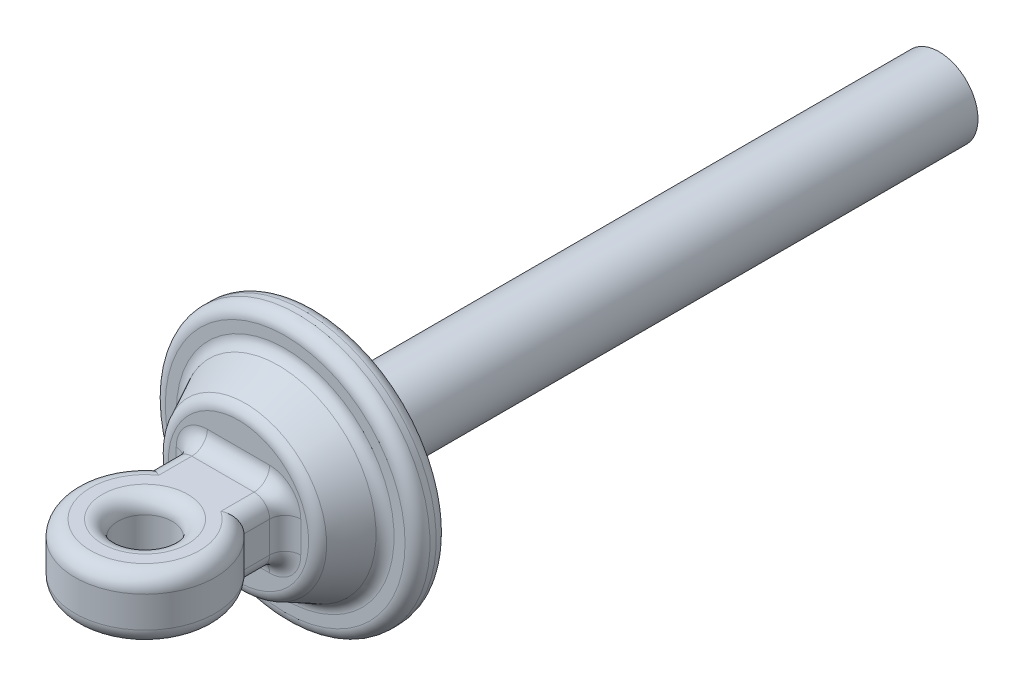
SolidWorks part; units mm, degrees
ref_plane "前视基准面" through (0, 0, 0) normal (0, 0, 1) x (1, 0, 0)
ref_plane "上视基准面" through (0, 0, 0) normal (0, 1, 0) x (1, 0, 0)
ref_plane "右视基准面" through (0, 0, 0) normal (1, 0, 0) x (0, 0, -1)
other "Configuration Table"
sketch "草图2" plane through (0, 0, 0) normal (0, 0, 1) x (1, 0, 0)
  circle A0 centre (0, 0) radius 2.5
  dimension "D1" = 5
extrude "凸台-拉伸1" add sketch "草图2" along normal blind 40
sketch "草图6" plane through (0, 0, 0) normal (0, 1, 0) x (1, 0, 0)
  line L0 (-2.5, -40) -> (2.5, -40) construction
  line L1 (0, -40) -> (7.7, -40)
  line L2 (0, -40) -> (0, -42)
  line L3 (6.9944, -42) -> (7.7, -42)
  line L4 (8.5, -40.8) -> (8.5, -41.2)
  line L5 (0, -42) -> (0, -45)
  line L6 (0, -45) -> (4.5056, -45)
  line L7 (5.2211, -44.5578) -> (6.2789, -42.4422)
  line L8 (0, -40) -> (0, -50040) construction
  arc A0 (4.5056, -45) -> (5.2211, -44.5578) centre (4.5056, -44.2) ccw
  arc A1 (6.2789, -42.4422) -> (6.9944, -42) centre (6.9944, -42.8) cw
  arc A2 (7.7, -40) -> (8.5, -40.8) centre (7.7, -40.8) cw
  arc A3 (7.7, -42) -> (8.5, -41.2) centre (7.7, -41.2) ccw
  point P12 (5, -45)
  point P15 (6.5, -42)
  point P18 (8.5, -40)
  point P21 (8.5, -42)
  dimension "D6" = 0.8
  dimension "D1" = 8.5
  dimension "D2" = 2
  dimension "D3" = 3
  dimension "D4" = 5
  dimension "D5" = 2
revolve "旋转2" add sketch "草图6" angle 360 about L8
sketch "草图8" plane through (0, 0, 0) normal (0, 1, 0) x (1, 0, 0)
  line L0 (-3, -45) -> (-3, -47.6459)
  line L1 (3, -45) -> (3, -47.6459)
  line L2 (-3, -45) -> (3, -45)
  line L3 (-4.5056, -45) -> (4.5056, -45) construction
  arc A0 (-3, -47.6459) -> (3, -47.6459) centre (0, -51) ccw
  circle A1 centre (0, -51) radius 1.75
  point P6 (0, -45)
  point P7 (0, -45)
  dimension "D1" = 9
  dimension "D2" = 6
extrude "凸台-拉伸4" add sketch "草图8" along normal mid plane 4 contours A0 L1 L2 L0 | A1
fillet "圆角2" radius 1 12 edges at (3, 0, 45) (-3, 0, 45) (0, 2, 52.75) (0, 2, 45) (3, 2, 46.3229) (0, 2, 55.5) (-3, 2, 46.3229) (0, -2, 52.75) (0, -2, 55.5) (3, -2, 46.3229) (0, -2, 45) (-3, -2, 46.3229)
